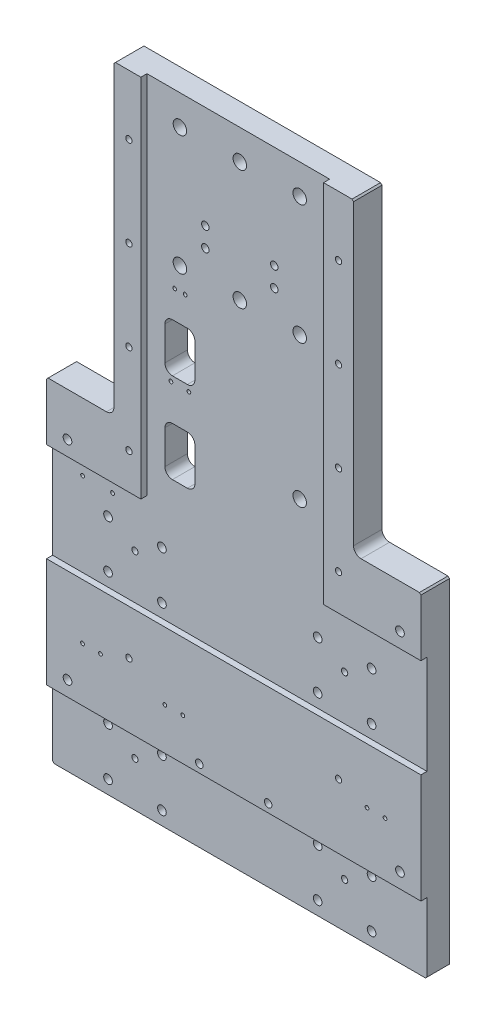
SolidWorks part; units mm, degrees
material "6061-T6 (SS)"
ref_plane "Front Plane" through (0, 0, 0) normal (0, 0, 1) x (1, 0, 0)
ref_plane "Top Plane" through (0, 0, 0) normal (0, 1, 0) x (1, 0, 0)
ref_plane "Right Plane" through (0, 0, 0) normal (1, 0, 0) x (0, 0, -1)
sketch "Sketch1" plane through (0, 0, 0) normal (0, 0, 1) x (1, 0, 0)
  line L0 (-143.6418, 90) -> (-30.2219, 90) construction
  line L1 (70, 60) -> (-70, 60) construction
  line L2 (70, 60) -> (70, -60) construction
  line L3 (70, -60) -> (-70, -60) construction
  line L4 (-70, 60) -> (-70, -60) construction
  line L5 (70, 60) -> (-70, -60) construction
  line L6 (70, -60) -> (-70, 60) construction
  line L7 (-88, 76) -> (-52, 76) construction
  line L8 (-88, 76) -> (-88, 44) construction
  line L9 (-88, 44) -> (-52, 44) construction
  line L10 (-52, 76) -> (-52, 44) construction
  line L11 (-88, 76) -> (-52, 44) construction
  line L12 (-88, 44) -> (-52, 76) construction
  line L13 (-125, 140) -> (-125, -85)
  line L14 (-125, -85) -> (125, -85)
  line L15 (125, -85) -> (125, 140)
  line L16 (125, 140) -> (80, 140)
  line L17 (80, 140) -> (80, 345)
  line L18 (80, 345) -> (-80, 345)
  line L19 (-80, 345) -> (-80, 140)
  line L20 (-80, 140) -> (-125, 140)
  line L21 (0, -10.4775) -> (0, 10.4775) construction
  line L22 (-311.1324, 118) -> (-279.0719, 118) construction
  point P0 (0, 0)
  point P19 (0, 345)
  dimension "D1" = 32
  dimension "D2" = 36
  dimension "D3" = 120
  dimension "D4" = 140
  dimension "D5" = 30
  dimension "D6" = 10
  dimension "D7" = 25
  dimension "D8" = 250
  dimension "D9" = 430
  dimension "D10" = 205
  dimension "D11" = 28
extrude "Boss-Extrude1" add sketch "Sketch1" along normal blind 19.05
sketch "Sketch2" plane through (0, 0, 19.05) normal (0, 0, 1) x (1, 0, 0)
  line L0 (125, -85) -> (125, 140) construction
  line L1 (-125, -85) -> (125, -85)
  line L2 (-125, -85) -> (-125, -38)
  line L3 (-125, -38) -> (125, -38)
  line L4 (125, -85) -> (125, -38)
  line L5 (-125, 35) -> (125, 35)
  line L6 (-125, 140) -> (-125, -85) construction
  line L7 (125, 35) -> (125, 101)
  line L8 (125, 101) -> (60, 101)
  line L9 (60, 101) -> (60, 345)
  line L10 (80, 345) -> (-80, 345) construction
  line L11 (60, 345) -> (-62, 345)
  line L12 (-62, 345) -> (-62, 101)
  line L13 (-62, 101) -> (-125, 101)
  line L14 (-125, 101) -> (-125, 35)
  line L15 (70, -60) -> (-70, -60) construction
  line L16 (70, 60) -> (-70, 60) construction
  line L18 (0, -10.4775) -> (0, 10.4775) construction
  line L19 (-200143.6418, 90) -> (199969.7781, 90) construction
  dimension "D1" = 22
  dimension "D2" = 25
  dimension "D3" = 60
  dimension "D4" = 62
  dimension "D5" = 11
extrude "Cut-Extrude1" cut sketch "Sketch2" against normal offset from surface (4.05 mm away) 15 up to face at (0, 135, 0)
hole_wizard "M5 Clearance Hole2" positions "Sketch3" profile "Sketch4" hole size "M5" standard "ANSI Metric" end condition up to next
sketch "Sketch3" plane through (0, 0, 15) normal (0, 0, 1) x (1, 0, 0)
  point P0 (-88, 76)
  point P3 (-52, 76)
  point P6 (-52, 44)
  point P9 (-88, 44)
sketch "Sketch4" plane through (-88, 76, 15) normal (1, 0, 0) x (0, -1, 0)
  line L0 (0, 0) -> (0, 15)
  line L1 (0, 15) -> (2.9, 15)
  line L2 (2.9, 15) -> (2.9, 0)
  line L5 (2.9, 0) -> (0, 0)
  line L11 (0, -6.35) -> (0, 107.95) construction
  dimension "Thru Hole Dia." = 5.8
  dimension "Thru Hole Depth" = 15
mirror "Mirror1" about plane through (0, 0, 0) normal (0, 1, 0) of "M5 Clearance Hole2"
hole_wizard "M5 Clearance Hole1" positions "Sketch15" profile "Sketch16" hole size "M5" standard "ANSI Metric" end condition up to next
sketch "Sketch15" plane through (0, 0, 19.05) normal (0, 0, 1) x (1, 0, 0)
  line L0 (-111, 111) -> (-111, -28)
  line L10 (125, -38) -> (-125, -38) construction
  line L11 (-62, 101) -> (-125, 101) construction
  line L12 (0, -10.4775) -> (0, 10.4775) construction
  point P1 (-111, 111)
  point P2 (-111, -28)
  dimension "D1" = 10
  dimension "D2" = 111
  dimension "D3" = 10
sketch "Sketch16" plane through (-111, 111, 19.05) normal (1, 0, 0) x (0, -1, 0)
  line L0 (0, 0) -> (0, 19.05)
  line L1 (0, 19.05) -> (2.9, 19.05)
  line L2 (2.9, 19.05) -> (2.9, 0)
  line L5 (2.9, 0) -> (0, 0)
  line L11 (0, -6.35) -> (0, 107.95) construction
  dimension "Thru Hole Dia." = 5.8
  dimension "Thru Hole Depth" = 19.05
hole_wizard "M5x0.8 Tapped Hole1" positions "Sketch5" profile "Sketch6" tap size "M5x0.8" standard "ANSI Metric" end condition up to next
sketch "Sketch5" plane through (0, 0, 19.05) normal (0, 0, 1) x (1, 0, 0)
  line L0 (-70, 60) -> (-70, -60) construction
  line L1 (-125, -85) -> (125, -85) construction
  point P0 (-70, -55)
  dimension "D1" = 30
sketch "Sketch6" plane through (-70, -55, 19.05) normal (1, 0, 0) x (0, -1, 0)
  line L0 (0, 0) -> (0, 19.05)
  line L1 (0, 19.05) -> (2.1, 19.05)
  line L2 (2.1, 19.05) -> (2.1, 0)
  line L5 (2.1, 0) -> (0, 0)
  line L11 (0, -6.35) -> (0, 107.95) construction
  dimension "Thru Tap Drill Dia." = 4.2
  dimension "Thru Tap Drill Depth" = 19.05
cosmetic thread "Hole Thread9" parameters "D2"=5
pattern_linear "LPattern1" count 7 spacing 60 along (0, 1, 0) of "M5x0.8 Tapped Hole1"
cosmetic thread "Hole Thread10" parameters "D2"=5
cosmetic thread "Hole Thread11" parameters "D2"=5
cosmetic thread "Hole Thread12" parameters "D2"=5
mirror "Mirror2" about plane through (0, 0, 0) normal (1, 0, 0) of "LPattern1", "Mirror1", "M5 Clearance Hole1", "M5 Clearance Hole2", "M5x0.8 Tapped Hole1"
cosmetic thread "Hole Thread13" parameters "D2"=5
cosmetic thread "Hole Thread14" parameters "D2"=5
cosmetic thread "Hole Thread15" parameters "D2"=5
cosmetic thread "Hole Thread19" parameters "D2"=5
hole_wizard "M8 Clearance Hole1" positions "Sketch7" profile "Sketch8" hole size "M8" standard "ANSI Metric" end condition up to next
sketch "Sketch7" plane through (0, 0, 15) normal (0, 0, 1) x (1, 0, 0)
  line L1 (-40, 325) -> (40, 325)
  line L2 (40, 325) -> (40, 245)
  line L3 (40, 245) -> (40, 150)
  line L6 (40, 245) -> (-40, 245)
  line L8 (-40, 245) -> (-40, 325)
  line L10 (0, -10.4775) -> (0, 10.4775) construction
  line L11 (80, 345) -> (-80, 345) construction
  point P2 (-40, 325)
  point P4 (40, 325)
  point P6 (40, 245)
  point P7 (40, 150)
  point P13 (-40, 245)
  point P34 (0, 325)
  point P35 (0, 245)
  dimension "D1" = 80
  dimension "D2" = 80
  dimension "D3" = 95
  dimension "D4" = 20
sketch "Sketch8" plane through (-40, 325, 15) normal (1, 0, 0) x (0, -1, 0)
  line L0 (0, 0) -> (0, 15)
  line L1 (0, 15) -> (4.5, 15)
  line L2 (4.5, 15) -> (4.5, 0)
  line L5 (4.5, 0) -> (0, 0)
  line L11 (0, -6.35) -> (0, 107.95) construction
  dimension "Thru Hole Dia." = 9
  dimension "Thru Hole Depth" = 15
hole_wizard "M6x1.0 Tapped Hole2" positions "Sketch9" profile "Sketch10" tap size "M6x1.0" standard "ANSI Metric" end condition up to next
sketch "Sketch9" plane through (0, 0, 19.05) normal (0, 0, 1) x (1, 0, 0)
  line L1 (-23, 276.5) -> (23, 276.5)
  line L2 (-23, 276.5) -> (-23, 263.5)
  line L3 (-23, 263.5) -> (23, 263.5)
  line L4 (23, 276.5) -> (23, 263.5)
  line L5 (0, -10.4775) -> (0, 10.4775) construction
  line L6 (80, 345) -> (-80, 345) construction
  line L7 (-23, -32.5) -> (23, -32.5)
  point P2 (-23, 276.5)
  point P3 (23, 263.5)
  point P68 (-23, 263.5)
  point P69 (23, 276.5)
  point P70 (0, 276.5)
  point P75 (-23, 270)
  point P85 (-23, -32.5)
  point P86 (23, -32.5)
  dimension "D1" = 13
  dimension "D2" = 46
  dimension "D3" = 75
  dimension "D4" = 302.5
sketch "Sketch10" plane through (-23, 276.5, 19.05) normal (1, 0, 0) x (0, -1, 0)
  line L0 (0, 0) -> (0, 19.05)
  line L1 (0, 19.05) -> (2.5, 19.05)
  line L2 (2.5, 19.05) -> (2.5, 0)
  line L5 (2.5, 0) -> (0, 0)
  line L11 (0, -6.35) -> (0, 107.95) construction
  dimension "Thru Tap Drill Dia." = 5
  dimension "Thru Tap Drill Depth" = 19.05
cosmetic thread "Hole Thread27" parameters "D2"=6
cosmetic thread "Hole Thread28" parameters "D2"=6
cosmetic thread "Hole Thread29" parameters "D2"=6
cosmetic thread "Hole Thread30" parameters "D2"=6
cosmetic thread "Hole Thread31" parameters "D2"=6
cosmetic thread "Hole Thread32" parameters "D2"=6
hole_wizard "M3x0.5 Tapped Hole3" positions "Sketch21" profile "Sketch22" tap size "M3x0.5" standard "ANSI Metric" end condition through all
sketch "Sketch21" plane through (0, 0, 19.05) normal (0, 0, 1) x (1, 0, 0)
  line L0 (-101, -2) -> (-89, -2)
  line L2 (70, -60) -> (-70, -60) construction
  line L4 (89, -2) -> (101, -2)
  line L7 (-89, -2) -> (89, -2)
  line L9 (0, -10.4775) -> (0, 10.4775) construction
  line L10 (-125, 35) -> (-125, -38) construction
  point P1 (-101, -2)
  point P2 (-89, -2)
  point P10 (89, -2)
  point P11 (101, -2)
  point P29 (0, -2)
  point P35 (-95, -2)
  dimension "D1" = 12
  dimension "D2" = 58
  dimension "D3" = 30
cosmetic thread "Hole Thread49" parameters "D1"=10, "D2"=3
cosmetic thread "Hole Thread50" parameters "D1"=10, "D2"=3
cosmetic thread "Hole Thread51" parameters "D1"=10, "D2"=3
cosmetic thread "Hole Thread52" parameters "D1"=10, "D2"=3
sketch "Sketch22" plane through (-101, -2, 19.05) normal (1, 0, 0) x (0, -1, 0)
  line L0 (0, 0) -> (0, 19.05)
  line L1 (0, 19.05) -> (1.25, 19.05)
  line L2 (1.25, 19.05) -> (1.25, 0)
  line L5 (1.25, 0) -> (0, 0)
  line L11 (0, -6.35) -> (0, 107.95) construction
  dimension "Thru Tap Drill Dia." = 2.5
  dimension "Thru Tap Drill Depth" = 19.05
hole_wizard "M3x0.5 Tapped Hole1" positions "Sketch11" profile "Sketch12" tap size "M3x0.5" standard "ANSI Metric" end condition through all
sketch "Sketch11" plane through (0, 0, 15) normal (0, 0, 1) x (1, 0, 0)
  line L0 (-105, 91) -> (-85, 91)
  line L7 (-125, 140) -> (-125, -85) construction
  line L8 (-125, 101) -> (-62, 101) construction
  point P1 (-105, 91)
  point P2 (-85, 91)
  point P18 (-95, 91)
  dimension "D1" = 20
  dimension "D2" = 10
  dimension "D4" = 30
cosmetic thread "Hole Thread35" parameters "D1"=10, "D2"=3
cosmetic thread "Hole Thread36" parameters "D1"=10, "D2"=3
sketch "Sketch12" plane through (-105, 91, 15) normal (1, 0, 0) x (0, -1, 0)
  line L0 (0, 0) -> (0, 15)
  line L1 (0, 15) -> (1.25, 15)
  line L2 (1.25, 15) -> (1.25, 0)
  line L5 (1.25, 0) -> (0, 0)
  line L11 (0, -6.35) -> (0, 107.95) construction
  dimension "Thru Tap Drill Dia." = 2.5
  dimension "Thru Tap Drill Depth" = 15
hole_wizard "M3x0.5 Tapped Hole2" positions "Sketch18" profile "Sketch19" tap size "M3x0.5" standard "ANSI Metric" end condition up to next
sketch "Sketch18" plane through (0, 0, 0) normal (0, 0, 1) x (1, 0, 0)
  line L0 (-43.5, 230) -> (-36.5, 230)
  line L2 (0, -10.4775) -> (0, 10.4775) construction
  line L3 (10.4775, 0) -> (-10.4775, 0) construction
  point P0 (-43.5, 230)
  point P1 (-36.5, 230)
  point P4 (-40, 230)
  dimension "D1" = 7
  dimension "D2" = 40
  dimension "D3" = 230
sketch "Sketch19" plane through (-43.5, 230, 0) normal (1, 0, 0) x (0, 1, 0)
  line L0 (0, 0) -> (0, 15)
  line L1 (0, 15) -> (1.25, 15)
  line L2 (1.25, 15) -> (1.25, 0)
  line L5 (1.25, 0) -> (0, 0)
  line L11 (0, -6.35) -> (0, 107.95) construction
  dimension "Thru Tap Drill Dia." = 2.5
  dimension "Thru Tap Drill Depth" = 15
cosmetic thread "Hole Thread57" parameters "D1"=12, "D2"=3
cosmetic thread "Hole Thread58" parameters "D1"=12, "D2"=3
sketch "Sketch20" plane through (0, 0, 15) normal (0, 0, 1) x (1, 0, 0)
  line L3 (-43.5, 230) -> (-36.5, 230) construction
  line L4 (-50, 206.25) -> (-50, 183.75)
  line L7 (-45, 178.75) -> (-35, 178.75)
  line L8 (-30, 183.75) -> (-30, 206.25)
  line L9 (-35, 211.25) -> (-45, 211.25)
  line L10 (-50, 146.25) -> (-50, 123.75)
  line L11 (-45, 118.75) -> (-35, 118.75)
  line L12 (-30, 123.75) -> (-30, 146.25)
  line L13 (-35, 151.25) -> (-45, 151.25)
  line L14 (-40, 211.25) -> (-40, 230) construction
  arc A4 (-50, 206.25) -> (-45, 211.25) centre (-45, 206.25) cw
  arc A5 (-30, 206.25) -> (-35, 211.25) centre (-35, 206.25) ccw
  arc A6 (-35, 178.75) -> (-30, 183.75) centre (-35, 183.75) ccw
  arc A7 (-50, 183.75) -> (-45, 178.75) centre (-45, 183.75) ccw
  arc A8 (-50, 123.75) -> (-45, 118.75) centre (-45, 123.75) ccw
  arc A9 (-35, 118.75) -> (-30, 123.75) centre (-35, 123.75) ccw
  arc A10 (-30, 146.25) -> (-35, 151.25) centre (-35, 146.25) ccw
  arc A11 (-50, 146.25) -> (-45, 151.25) centre (-45, 146.25) cw
  point P17 (-30, 178.75)
  point P20 (-50, 178.75)
  point P29 (-50, 195)
  point P32 (-50, 135)
  dimension "D1" = 5
  dimension "D2" = 32.5
  dimension "D3" = 35
  dimension "D4" = 20
  dimension "D5" = 60
extrude "Cut-Extrude2" cut sketch "Sketch20" against normal up to next
hole_wizard "M3x0.5 Tapped Hole4" positions "Sketch23" profile "Sketch24" tap size "M3x0.5" standard "ANSI Metric"
sketch "Sketch23" plane through (0, 0, 0) normal (0, 0, -1) x (-1, 0, 0)
  line L0 (34, 175) -> (46, 175)
  line L3 (40, 175) -> (40, -10)
  line L6 (34, -10) -> (46, -10)
  line L11 (-70, -60) -> (70, -60) construction
  line L12 (40, 211.25) -> (40, 230) construction
  point P1 (34, 175)
  point P2 (46, 175)
  point P11 (34, -10)
  point P12 (46, -10)
  dimension "D1" = 185
  dimension "D2" = 12
  dimension "D3" = 50
sketch "Sketch24" plane through (-34, 175, 0) normal (1, 0, 0) x (0, 1, 0)
  line L0 (0, 0) -> (0, 15)
  line L1 (0, 15) -> (1.25, 15)
  line L2 (1.25, 15) -> (1.25, 0)
  line L5 (1.25, 0) -> (0, 0)
  line L11 (0, -6.35) -> (0, 107.95) construction
  dimension "Thru Tap Drill Dia." = 2.5
  dimension "Thru Tap Drill Depth" = 15
cosmetic thread "Hole Thread53" parameters "D1"=10, "D2"=3
cosmetic thread "Hole Thread54" parameters "D1"=10, "D2"=3
cosmetic thread "Hole Thread55" parameters "D1"=10, "D2"=3
cosmetic thread "Hole Thread56" parameters "D1"=10, "D2"=3
fillet "Fillet1" radius 5 2 edges at (80, 140, 9.525) (-80, 140, 9.525)
chamfer "Chamfer1" distance 1 angle 45 6 edges at (125, 140, 9.525) (125, -85, 7.5) (-125, -85, 7.5) (-125, 140, 9.525) (80, 345, 9.525) (-80, 345, 9.525)
